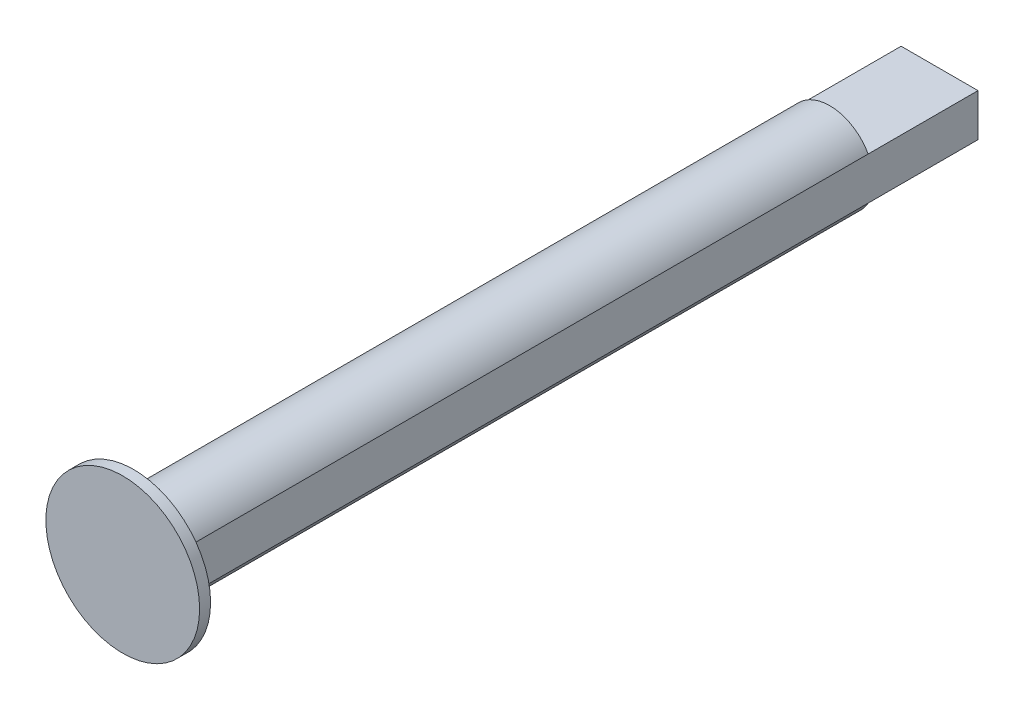
SolidWorks part; units mm, degrees
ref_plane "Front Plane" through (0, 0, 0) normal (0, 0, 1) x (1, 0, 0)
ref_plane "Top Plane" through (0, 0, 0) normal (0, 1, 0) x (1, 0, 0)
ref_plane "Right Plane" through (0, 0, 0) normal (1, 0, 0) x (0, 0, -1)
sketch "Sketch1" plane through (0, 0, 0) normal (0, 0, 1) x (1, 0, 0)
  line L0 (3.5, -1.9365) -> (3.5, 1.9365)
  arc A0 (3.5, 1.9365) -> (3.5, -1.9365) centre (0, 0) ccw
  arc A1 (3.5, -1.9365) -> (3.5, 1.9365) centre (0, 0) ccw construction
  dimension "D1" = 8
  dimension "D2" = 3.5
extrude "Boss-Extrude1" add sketch "Sketch1" against normal blind 73.3796
sketch "Sketch2" plane through (0, 0, 0) normal (0, 0, 1) x (1, 0, 0)
  circle A0 centre (0, 0) radius 7
  dimension "D1" = 14
extrude "Boss-Extrude2" add sketch "Sketch2" along normal blind 1
sketch "Sketch3" plane through (0, 0, -73.3796) normal (0, 0, -1) x (-1, 0, 0)
  line L0 (-3.5, -1.9365) -> (-3.5, 1.9365) construction
  line L1 (-3.5, -1.9365) -> (-3.5, 1.9365) construction
  line L2 (-3.5, 1.9365) -> (3.5, 1.9365)
  line L3 (-3.5, -1.9365) -> (3.5, -1.9365)
  arc A0 (-3.5, -1.9365) -> (-3.5, 1.9365) centre (0, 0) ccw construction
  arc A1 (-3.5, -1.9365) -> (3.5, -1.9365) centre (0, 0) ccw
  arc A2 (3.5, -1.9365) -> (3.5, 1.9365) centre (0, 0) ccw construction
  arc A3 (3.5, 1.9365) -> (-3.5, 1.9365) centre (0, 0) ccw
  point P7 (0, 0)
  point P8 (0, 0)
extrude "Cut-Extrude1" cut sketch "Sketch3" against normal blind 10
